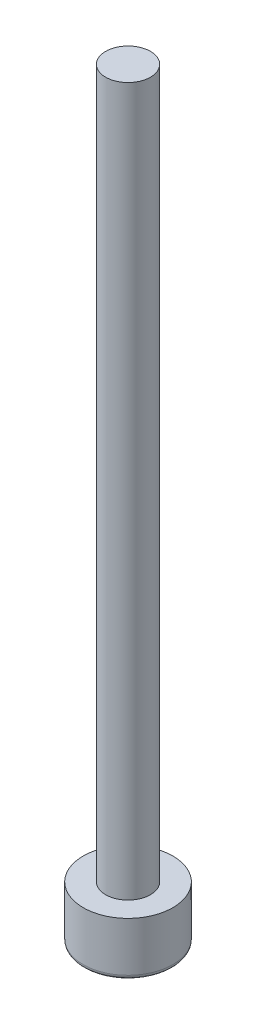
SolidWorks part; units mm, degrees
material "Plain Carbon Steel"
ref_plane "Front Plane" through (0, 0, 0) normal (0, 0, 1) x (1, 0, 0)
ref_plane "Top Plane" through (0, 0, 0) normal (0, 1, 0) x (1, 0, 0)
ref_plane "Right Plane" through (0, 0, 0) normal (1, 0, 0) x (0, 0, -1)
sketch "Sketch1" plane through (0, 0, 0) normal (0, 0, 1) x (1, 0, 0)
  line L0 (0, 0) -> (0, 55.6818) construction
  line L1 (0, 170) -> (5, 170)
  line L2 (5, 170) -> (5, 12)
  line L3 (5, 12) -> (10, 12)
  line L4 (10, 12) -> (10, 0)
  line L5 (10, 0) -> (0, 0)
  line L6 (0, 0) -> (0, 170)
  dimension "D1" = 20
  dimension "D2" = 12
  dimension "D3" = 10
  dimension "D4" = 170
revolve "Revolve1" add sketch "Sketch1" angle 360 about L0
fillet "Fillet1" radius 1 1 edges at (0, 0, -10)
